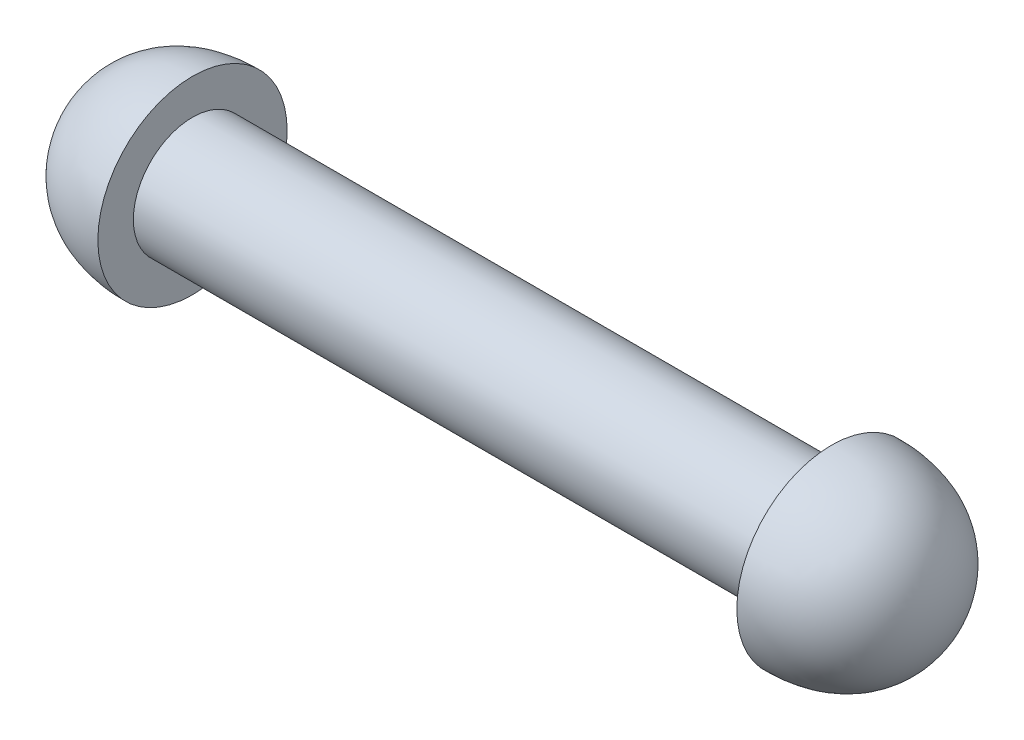
SolidWorks part; units mm, degrees
material "Plain Carbon Steel"
ref_plane "Front Plane" through (0, 0, 0) normal (0, 0, 1) x (1, 0, 0)
ref_plane "Top Plane" through (0, 0, 0) normal (0, 1, 0) x (1, 0, 0)
ref_plane "Right Plane" through (0, 0, 0) normal (1, 0, 0) x (0, 0, -1)
sketch "Sketch1" plane through (0, 0, 0) normal (1, 0, 0) x (0, 0, -1)
  circle A0 centre (0, 0) radius 25
  dimension "D1" = 50
extrude "Boss-Extrude1" add sketch "Sketch1" along normal blind 135
sketch "Sketch3" plane through (0, 0, 0) normal (0, 0, 1) x (1, 0, 0)
  line L2 (-100.0787, 0) -> (83.5342, 0) construction
  line L3 (0, 0) -> (-45.4584, 0)
  line L4 (0, 40) -> (0, 0)
  spline S0 degree 3 poles (-45.4584, 0) (-45.4584, 20.1838) (-30.9912, 40) (0, 40) knots 0 0 0 0 1 1 1 1
  dimension "D1" = 40
revolve "Revolve1" add sketch "Sketch3" angle 360 about L2
mirror "Mirror1" about plane through (135, 0, 0) normal (1, 0, 0) of "Boss-Extrude1", "Revolve1"
